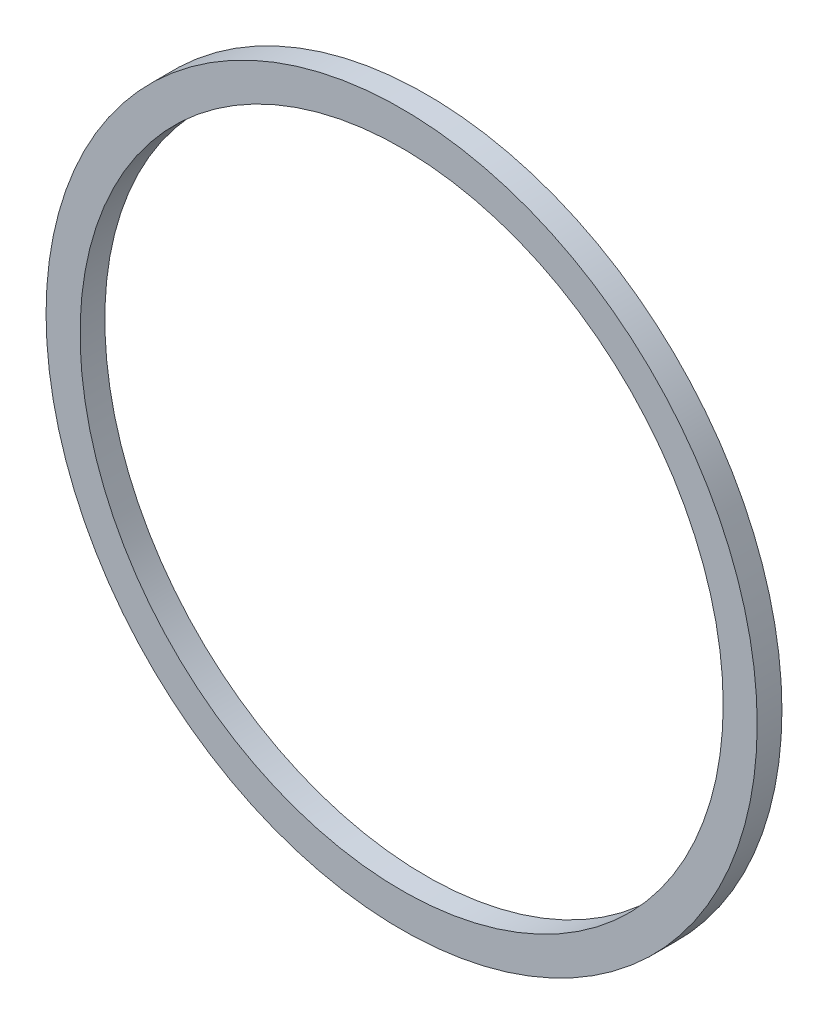
SolidWorks part; units mm, degrees
ref_plane "Front" through (0, 0, 0) normal (0, 0, 1) x (1, 0, 0)
ref_plane "Top" through (0, 0, 0) normal (0, 1, 0) x (1, 0, 0)
ref_plane "Right" through (0, 0, 0) normal (1, 0, 0) x (0, 0, -1)
sketch "Sketch1" plane through (0, 0, 0) normal (0, 0, 1) x (1, 0, 0)
  circle A0 centre (0, 0) radius 6.5
  circle A1 centre (0, 0) radius 7.1875
  dimension "D1" = 13
extrude "Extrude1" add sketch "Sketch1" along normal blind 0.5
